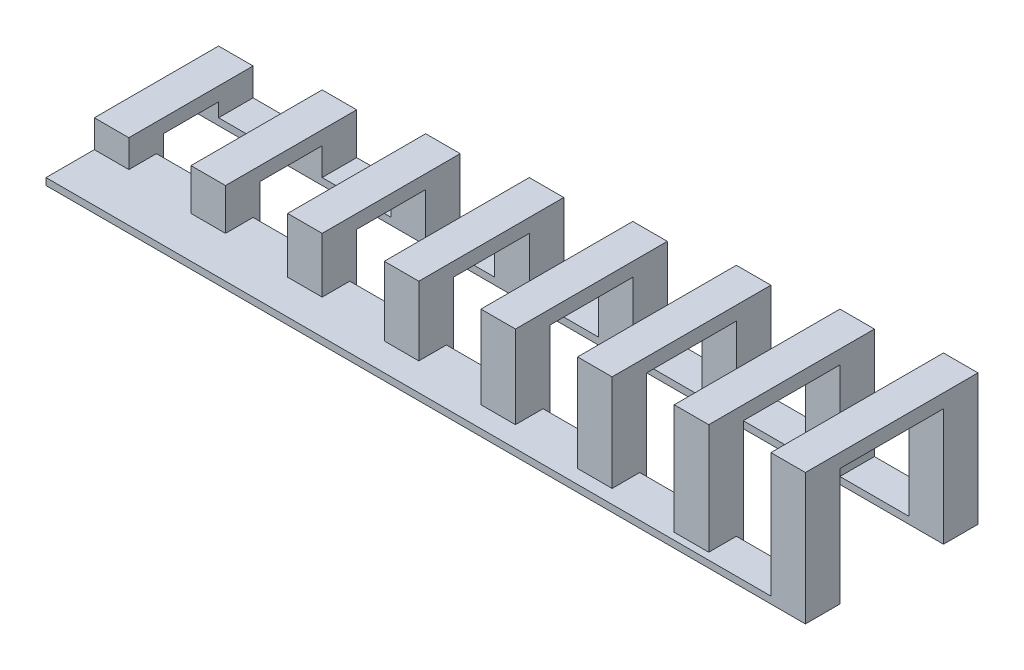
SolidWorks part; units mm, degrees
ref_plane "Front Plane" through (0, 0, 0) normal (0, 0, 1) x (1, 0, 0)
ref_plane "Top Plane" through (0, 0, 0) normal (0, 1, 0) x (1, 0, 0)
ref_plane "Right Plane" through (0, 0, 0) normal (1, 0, 0) x (0, 0, -1)
sketch "Sketch1" plane through (0, 0, 0) normal (0, 1, 0) x (1, 0, 0)
  line L1 (0, 0) -> (110, 0)
  line L2 (0, 0) -> (0, 25)
  line L3 (0, 25) -> (110, 25)
  line L4 (110, 0) -> (110, 25)
  dimension "D1" = 25
  dimension "D2" = 110
extrude "Base" add sketch "Sketch1" along normal blind 1 contours L2 L3 L4 L1
sketch "Sketch10" plane through (0, 1, 0) normal (0, 1, 0) x (1, 0, 0)
  line L1 (0, 25) -> (5, 25)
  line L2 (0, 25) -> (0, 20)
  line L3 (0, 20) -> (5, 20)
  line L4 (5, 25) -> (5, 20)
  line L9 (0, 0) -> (0, 25) construction
  line L42 (0, 12) -> (5, 12)
  line L43 (0, 12) -> (0, 7)
  line L44 (0, 7) -> (5, 7)
  line L45 (5, 12) -> (5, 7)
  dimension "D1" = 5
  dimension "D2" = 5
  dimension "D24" = 5
  dimension "D25" = 5
  dimension "D26" = 8
extrude "leg1" add sketch "Sketch10" along normal blind 4
sketch "leg2" plane through (0, 1, 0) normal (0, 1, 0) x (1, 0, 0)
  line L0 (5, 25) -> (110, 25) construction
  line L1 (15, 25) -> (20, 25)
  line L2 (15, 25) -> (15, 20)
  line L3 (15, 20) -> (20, 20)
  line L4 (20, 25) -> (20, 20)
  line L5 (5, 20) -> (5, 25) construction
  line L7 (15, 11) -> (20, 11)
  line L8 (15, 11) -> (15, 6)
  line L9 (15, 6) -> (20, 6)
  line L10 (20, 11) -> (20, 6)
  dimension "D1" = 10
  dimension "D2" = 5
  dimension "D3" = 5
  dimension "D4" = 9
  dimension "D5" = 5
  dimension "D6" = 5
sketch "leg3" plane through (0, 1, 0) normal (0, 1, 0) x (1, 0, 0)
  line L0 (5, 25) -> (110, 25) construction
  line L1 (30, 25) -> (35, 25)
  line L2 (30, 25) -> (30, 20)
  line L3 (30, 20) -> (35, 20)
  line L4 (35, 25) -> (35, 20)
  line L5 (20, 25) -> (20, 20) construction
  line L11 (30, 10) -> (35, 10)
  line L12 (30, 10) -> (30, 5)
  line L13 (30, 5) -> (35, 5)
  line L14 (35, 10) -> (35, 5)
  dimension "D1" = 10
  dimension "D2" = 5
  dimension "D3" = 5
  dimension "D4" = 10
  dimension "D5" = 5
  dimension "D6" = 5
sketch "leg4" plane through (0, 1, 0) normal (0, 1, 0) x (1, 0, 0)
  line L0 (5, 25) -> (110, 25) construction
  line L1 (45, 25) -> (50, 25)
  line L2 (45, 25) -> (45, 20)
  line L3 (45, 20) -> (50, 20)
  line L4 (50, 25) -> (50, 20)
  line L5 (35, 25) -> (35, 20) construction
  line L7 (45, 9) -> (50, 9)
  line L8 (45, 9) -> (45, 4)
  line L9 (45, 4) -> (50, 4)
  line L10 (50, 9) -> (50, 4)
  dimension "D1" = 10
  dimension "D2" = 5
  dimension "D3" = 5
  dimension "D4" = 11
  dimension "D5" = 5
  dimension "D6" = 5
sketch "leg5" plane through (0, 1, 0) normal (0, 1, 0) x (1, 0, 0)
  line L0 (5, 25) -> (110, 25) construction
  line L1 (60, 25) -> (65, 25)
  line L2 (60, 25) -> (60, 20)
  line L3 (60, 20) -> (65, 20)
  line L4 (65, 25) -> (65, 20)
  line L5 (50, 25) -> (50, 20) construction
  line L7 (60, 8) -> (65, 8)
  line L8 (60, 8) -> (60, 3)
  line L9 (60, 3) -> (65, 3)
  line L10 (65, 8) -> (65, 3)
  point P12 (0, 0)
  dimension "D1" = 10
  dimension "D2" = 5
  dimension "D3" = 5
  dimension "D4" = 12
  dimension "D5" = 5
  dimension "D6" = 5
sketch "leg6" plane through (0, 1, 0) normal (0, 1, 0) x (1, 0, 0)
  line L0 (5, 25) -> (110, 25) construction
  line L1 (75, 25) -> (80, 25)
  line L2 (75, 25) -> (75, 20)
  line L3 (75, 20) -> (80, 20)
  line L4 (80, 25) -> (80, 20)
  line L5 (65, 25) -> (65, 20) construction
  line L7 (75, 7) -> (80, 7)
  line L8 (75, 7) -> (75, 2)
  line L9 (75, 2) -> (80, 2)
  line L10 (80, 7) -> (80, 2)
  dimension "D1" = 10
  dimension "D2" = 5
  dimension "D3" = 5
  dimension "D4" = 13
  dimension "D5" = 5
  dimension "D6" = 5
sketch "leg7" plane through (0, 1, 0) normal (0, 1, 0) x (1, 0, 0)
  line L0 (5, 25) -> (110, 25) construction
  line L1 (90, 25) -> (95, 25)
  line L2 (90, 25) -> (90, 20)
  line L3 (90, 20) -> (95, 20)
  line L4 (95, 25) -> (95, 20)
  line L5 (80, 25) -> (80, 20) construction
  line L7 (90, 6) -> (95, 6)
  line L8 (90, 6) -> (90, 1)
  line L9 (90, 1) -> (95, 1)
  line L10 (95, 6) -> (95, 1)
  dimension "D1" = 10
  dimension "D2" = 5
  dimension "D3" = 5
  dimension "D4" = 14
  dimension "D5" = 5
  dimension "D6" = 5
sketch "leg8" plane through (0, 1, 0) normal (0, 1, 0) x (1, 0, 0)
  line L0 (95, 25) -> (95, 20) construction
  line L1 (110, 25) -> (105, 25)
  line L2 (110, 25) -> (110, 20)
  line L3 (110, 20) -> (105, 20)
  line L4 (105, 25) -> (105, 20)
  line L6 (110, 0) -> (105, 0)
  line L7 (110, 0) -> (110, 5)
  line L8 (110, 5) -> (105, 5)
  line L9 (105, 0) -> (105, 5)
  dimension "D1" = 10
  dimension "D2" = 5
  dimension "D3" = 5
extrude "leg2e" add sketch "leg2" along normal blind 6
extrude "leg3e" add sketch "leg3" along normal blind 8
extrude "leg4e" add sketch "leg4" along normal blind 10
extrude "leg5e" add sketch "leg5" along normal blind 12
extrude "leg6e" add sketch "leg6" along normal blind 14
extrude "leg7e" add sketch "leg7" along normal blind 16
extrude "leg8e" add sketch "leg8" along normal blind 18
sketch "Sketch29" plane through (0, 0, -20) normal (0, 0, 1) x (1, 0, 0)
  line L0 (5, 5) -> (5, 1) construction
  line L1 (0, 5) -> (5, 5)
  line L2 (0, 5) -> (0, 3)
  line L3 (0, 3) -> (5, 3)
  line L4 (5, 5) -> (5, 3)
  dimension "D1" = 2
sketch "Sketch30" plane through (0, 0, -20) normal (0, 0, 1) x (1, 0, 0)
  line L0 (20, 7) -> (20, 1) construction
  line L1 (15, 7) -> (20, 7)
  line L2 (15, 7) -> (15, 5)
  line L3 (15, 5) -> (20, 5)
  line L4 (20, 7) -> (20, 5)
  dimension "D1" = 2
sketch "Sketch31" plane through (0, 0, -20) normal (0, 0, 1) x (1, 0, 0)
  line L0 (35, 9) -> (35, 1) construction
  line L1 (30, 9) -> (35, 9)
  line L2 (30, 9) -> (30, 7)
  line L3 (30, 7) -> (35, 7)
  line L4 (35, 9) -> (35, 7)
  dimension "D1" = 2
sketch "Sketch32" plane through (0, 0, -20) normal (0, 0, 1) x (1, 0, 0)
  line L0 (50, 11) -> (50, 1) construction
  line L1 (45, 11) -> (50, 11)
  line L2 (45, 11) -> (45, 9)
  line L3 (45, 9) -> (50, 9)
  line L4 (50, 11) -> (50, 9)
  dimension "D1" = 2
sketch "Sketch33" plane through (0, 0, -20) normal (0, 0, 1) x (1, 0, 0)
  line L0 (65, 13) -> (65, 1) construction
  line L1 (60, 13) -> (65, 13)
  line L2 (60, 13) -> (60, 11)
  line L3 (60, 11) -> (65, 11)
  line L4 (65, 13) -> (65, 11)
  dimension "D1" = 2
sketch "Sketch34" plane through (0, 0, -20) normal (0, 0, 1) x (1, 0, 0)
  line L0 (80, 15) -> (80, 1) construction
  line L1 (75, 15) -> (80, 15)
  line L2 (75, 15) -> (75, 13)
  line L3 (75, 13) -> (80, 13)
  line L4 (80, 15) -> (80, 13)
  dimension "D1" = 2
sketch "Sketch35" plane through (0, 0, -20) normal (0, 0, 1) x (1, 0, 0)
  line L0 (95, 17) -> (95, 1) construction
  line L1 (90, 17) -> (95, 17)
  line L2 (90, 17) -> (90, 15)
  line L3 (90, 15) -> (95, 15)
  line L4 (95, 17) -> (95, 15)
  dimension "D1" = 2
sketch "Sketch36" plane through (0, 0, -20) normal (0, 0, 1) x (1, 0, 0)
  line L0 (110, 19) -> (110, 1) construction
  line L1 (105, 19) -> (110, 19)
  line L2 (105, 19) -> (105, 17)
  line L3 (105, 17) -> (110, 17)
  line L4 (110, 19) -> (110, 17)
  dimension "D1" = 2
extrude "bridge1" add sketch "Sketch29" along normal blind 8
extrude "bridge2" add sketch "Sketch30" along normal blind 9
extrude "bridge3" add sketch "Sketch31" along normal blind 10
extrude "bridge4" add sketch "Sketch32" along normal blind 11
extrude "bridge5" add sketch "Sketch33" along normal blind 12
extrude "bridge6" add sketch "Sketch34" along normal blind 13
extrude "bridge7" add sketch "Sketch35" along normal blind 14
extrude "bridge8" add sketch "Sketch36" along normal blind 15
sketch "Sketch37" plane through (0, 1, 0) normal (0, 1, 0) x (1, 0, 0)
  line L0 (0, 20) -> (110, 20)
  line L1 (110, 20) -> (110, 5)
  line L2 (110, 5) -> (95, 5)
  line L3 (95, 1) -> (95, 6) construction
  line L4 (95, 5) -> (95, 6)
  line L5 (95, 6) -> (80, 6)
  line L6 (80, 2) -> (80, 7) construction
  line L7 (80, 6) -> (80, 7)
  line L8 (80, 7) -> (65, 7)
  line L9 (65, 3) -> (65, 8) construction
  line L10 (65, 7) -> (65, 8)
  line L11 (65, 8) -> (50, 8)
  line L12 (50, 4) -> (50, 9) construction
  line L13 (50, 8) -> (50, 9)
  line L14 (50, 9) -> (35, 9)
  line L15 (35, 5) -> (35, 10) construction
  line L16 (35, 9) -> (35, 10)
  line L17 (35, 10) -> (20, 10)
  line L18 (20, 6) -> (20, 11) construction
  line L19 (20, 10) -> (20, 11)
  line L20 (20, 11) -> (5, 11)
  line L21 (5, 7) -> (5, 12) construction
  line L22 (5, 11) -> (5, 12)
  line L23 (5, 12) -> (0, 12)
  line L24 (0, 12) -> (0, 20)
extrude "Cut-Extrude4" cut sketch "Sketch37" against normal through all
